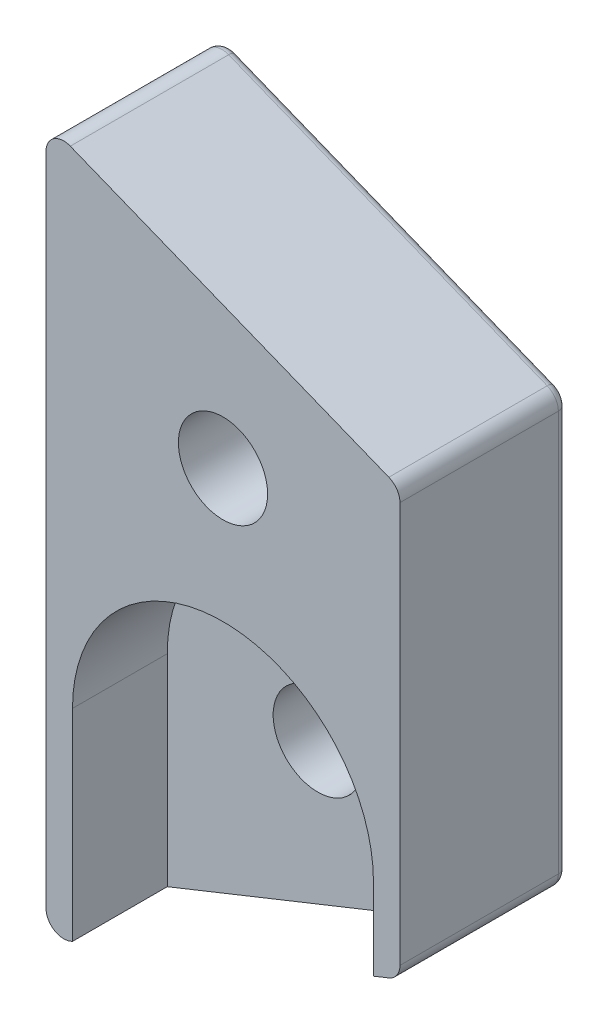
SolidWorks part; units mm, degrees
ref_plane "Front Plane" through (0, 0, 0) normal (0, 0, 1) x (1, 0, 0)
ref_plane "Top Plane" through (0, 0, 0) normal (0, 1, 0) x (1, 0, 0)
ref_plane "Right Plane" through (0, 0, 0) normal (1, 0, 0) x (0, 0, -1)
sketch "Sketch1" plane through (0, 0, 0) normal (0, 0, 1) x (1, 0, 0)
  line L0 (0, 0) -> (15.875, -6.35)
  line L1 (15.875, -6.35) -> (15.875, -25.4)
  line L2 (15.875, -25.4) -> (0, -31.75)
  line L3 (0, -31.75) -> (0, 0)
  line L4 (7.9375, -3.175) -> (7.9375, -9.525) construction
  line L5 (7.9375, -9.525) -> (7.9375, -22.225) construction
  line L6 (7.9375, -22.225) -> (7.9375, -28.575) construction
  circle A0 centre (7.9375, -22.225) radius 2
  circle A1 centre (7.9375, -9.525) radius 2
  dimension "D4" = 4
  dimension "D1" = 31.75
  dimension "D2" = 19.05
  dimension "D3" = 15.875
  dimension "D5" = 9.525
extrude "Boss-Extrude1" add sketch "Sketch1" along normal blind 7.5
fillet "Fillet1" radius 0.7937 4 edges at (0, -31.75, 3.75) (15.875, -25.4, 3.75) (15.875, -6.35, 3.75) (0, 0, 3.75)
sketch "Sketch2" plane through (0, 0, 7.5) normal (0, 0, 1) x (1, 0, 0)
  line L0 (14.6875, -22.225) -> (14.6875, -25.875)
  line L1 (1.0885, -31.3146) -> (15.376, -25.5996) construction
  line L2 (1.1875, -22.225) -> (1.1875, -31.275)
  line L3 (1.1875, -31.275) -> (14.6875, -25.875)
  arc A0 (14.6875, -22.225) -> (1.1875, -22.225) centre (7.9375, -22.225) ccw
  dimension "D1" = 13.5
extrude "Cut-Extrude1" cut sketch "Sketch2" against normal blind 4.25
fillet "Fillet2" radius 0.3969 8 edges at (15.7385, -6.4424, 0) (15.875, -15.875, 0) (15.7385, -25.3076, 0) (8.2323, -28.4571, 0) (0.3488, -31.2349, 0) (0, -15.875, 0) (0.3488, -0.5151, 0) (8.2323, -3.2929, 0)
mirror "Mirror1" [suppressed]
delete or keep bodies "Body-Delete/Keep 1" [suppressed] type delete bodies bodies 102
